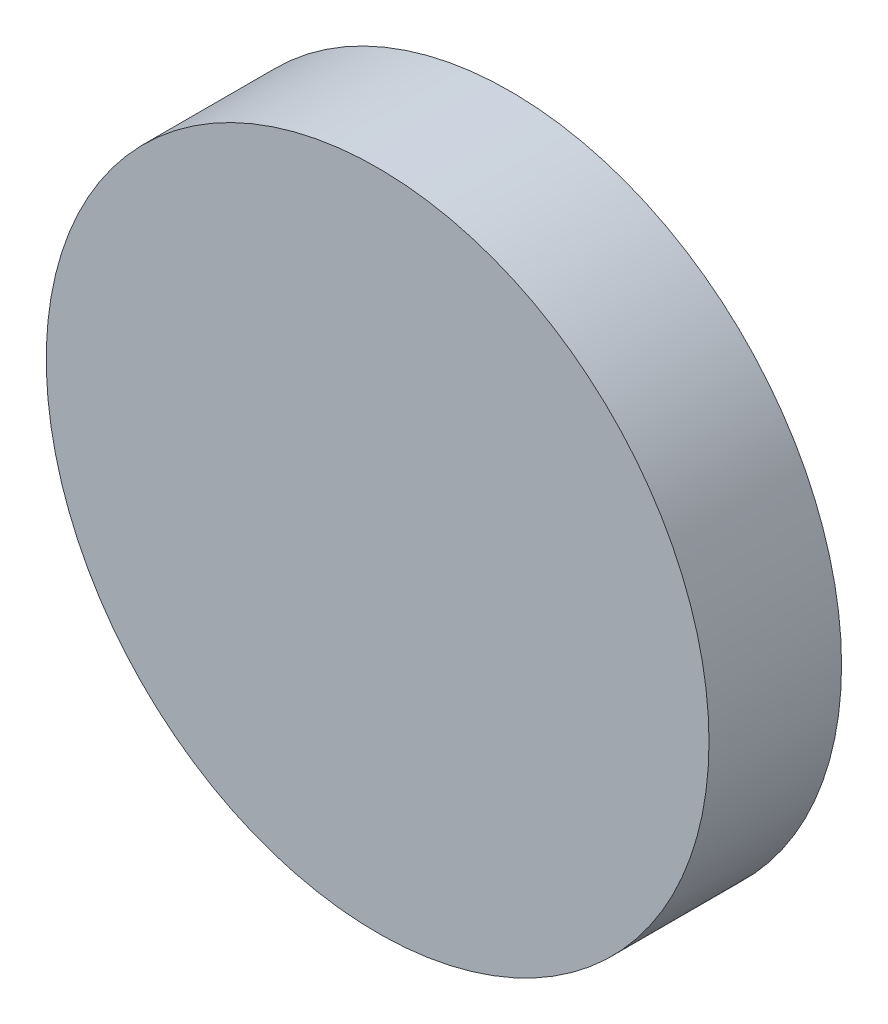
SolidWorks part; units mm, degrees
ref_plane "Front Plane" through (0, 0, 0) normal (0, 0, 1) x (1, 0, 0)
ref_plane "Top Plane" through (0, 0, 0) normal (0, 1, 0) x (1, 0, 0)
ref_plane "Right Plane" through (0, 0, 0) normal (1, 0, 0) x (0, 0, -1)
other "Configuration Table"
sketch "Sketch1" plane through (0, 0, 0) normal (0, 0, 1) x (1, 0, 0)
  circle A0 centre (1090, 1805) radius 100
extrude "STORE_sog2_kondenser_fan" add sketch "Sketch1" against normal blind 40 from offset 200 separate body
